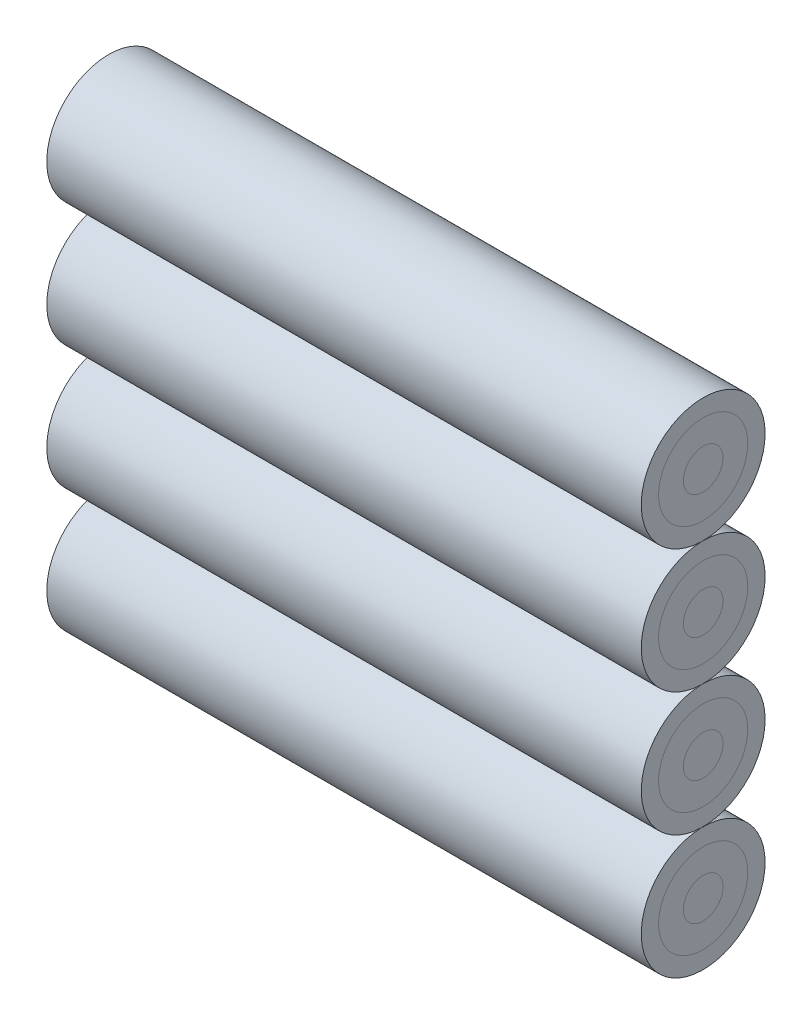
SolidWorks part; units mm, degrees
ref_plane "前视基准面" through (0, 0, 0) normal (0, 0, 1) x (1, 0, 0)
ref_plane "上视基准面" through (0, 0, 0) normal (0, 1, 0) x (1, 0, 0)
ref_plane "右视基准面" through (0, 0, 0) normal (1, 0, 0) x (0, 0, -1)
sketch "草图1" plane through (0, 0, 0) normal (1, 0, 0) x (0, 0, -1)
  circle A0 centre (0, 375) radius 125
  circle A1 centre (0, 125) radius 125
  circle A2 centre (0, -125) radius 125
  circle A3 centre (0, -375) radius 125
extrude "凸台-拉伸1" add sketch "草图1" along normal blind 1200 contours A3 | A0 | A1 | A2
sketch "草图2" plane through (1200, 0, 0) normal (1, 0, 0) x (0, 0, -1)
  circle A0 centre (0, 375) radius 90
  circle A1 centre (0, 125) radius 90
  circle A2 centre (0, -125) radius 90
  circle A3 centre (0, -375) radius 90
extrude "切除-拉伸1" cut sketch "草图2" against normal through all
sketch "草图3" plane through (0, 0, 0) normal (1, 0, 0) x (0, 0, -1)
  circle A0 centre (0, 375) radius 90
  circle A1 centre (0, 125) radius 90
  circle A2 centre (0, -125) radius 90
  circle A3 centre (0, -375) radius 90
extrude "凸台-拉伸3" add sketch "草图3" along normal blind 1200 separate body
sketch "草图4" plane through (1200, 0, 0) normal (1, 0, 0) x (0, 0, -1)
  circle A0 centre (0, 375) radius 40
  circle A1 centre (0, 125) radius 40
  circle A2 centre (0, -125) radius 40
  circle A3 centre (0, -375) radius 40
extrude "切除-拉伸2" cut sketch "草图4" against normal through all
sketch "草图5" plane through (0, 0, 0) normal (1, 0, 0) x (0, 0, -1)
  circle A0 centre (0, 375) radius 40
  circle A1 centre (0, 125) radius 40
  circle A2 centre (0, -125) radius 40
  circle A3 centre (0, -375) radius 40
extrude "凸台-拉伸7" add sketch "草图5" along normal blind 1200 separate body
